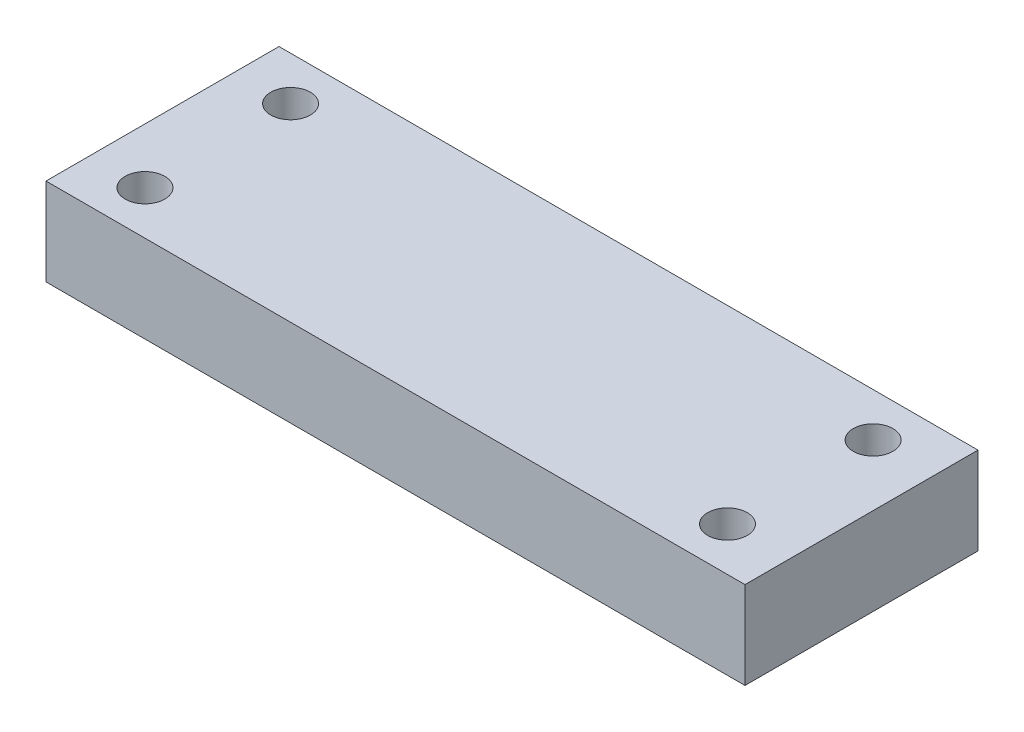
SolidWorks part; units mm, degrees
ref_plane "Front Plane" through (0, 0, 0) normal (0, 0, 1) x (1, 0, 0)
ref_plane "Top Plane" through (0, 0, 0) normal (0, 1, 0) x (1, 0, 0)
ref_plane "Right Plane" through (0, 0, 0) normal (1, 0, 0) x (0, 0, -1)
sketch "Sketch1" plane through (0, 0, 0) normal (0, 1, 0) x (1, 0, 0)
  line L1 (-38.1, 12.7) -> (38.1, 12.7)
  line L2 (-38.1, 12.7) -> (-38.1, -12.7)
  line L3 (-38.1, -12.7) -> (38.1, -12.7)
  line L4 (38.1, 12.7) -> (38.1, -12.7)
  dimension "D1" = 25.4
  dimension "D2" = 76.2
  dimension "D3" = 38.1
  dimension "D4" = 12.7
extrude "Boss-Extrude1" add sketch "Sketch1" along normal blind 9.525
sketch "Sketch2" plane through (0, 9.525, 0) normal (0, 1, 0) x (1, 0, 0)
  circle A0 centre (-32.0741, 7.9375) radius 2.159
  circle A1 centre (-32.0741, -7.9375) radius 2.159
  circle A2 centre (31.4259, 7.9375) radius 2.159
  circle A3 centre (31.4259, -7.9375) radius 2.159
  dimension "D1" = 4.318
  dimension "D2" = 15.875
  dimension "D3" = 63.5
  dimension "D4" = 32.0741
  dimension "D5" = 7.9375
extrude "Cut-Extrude1" cut sketch "Sketch2" against normal through all
